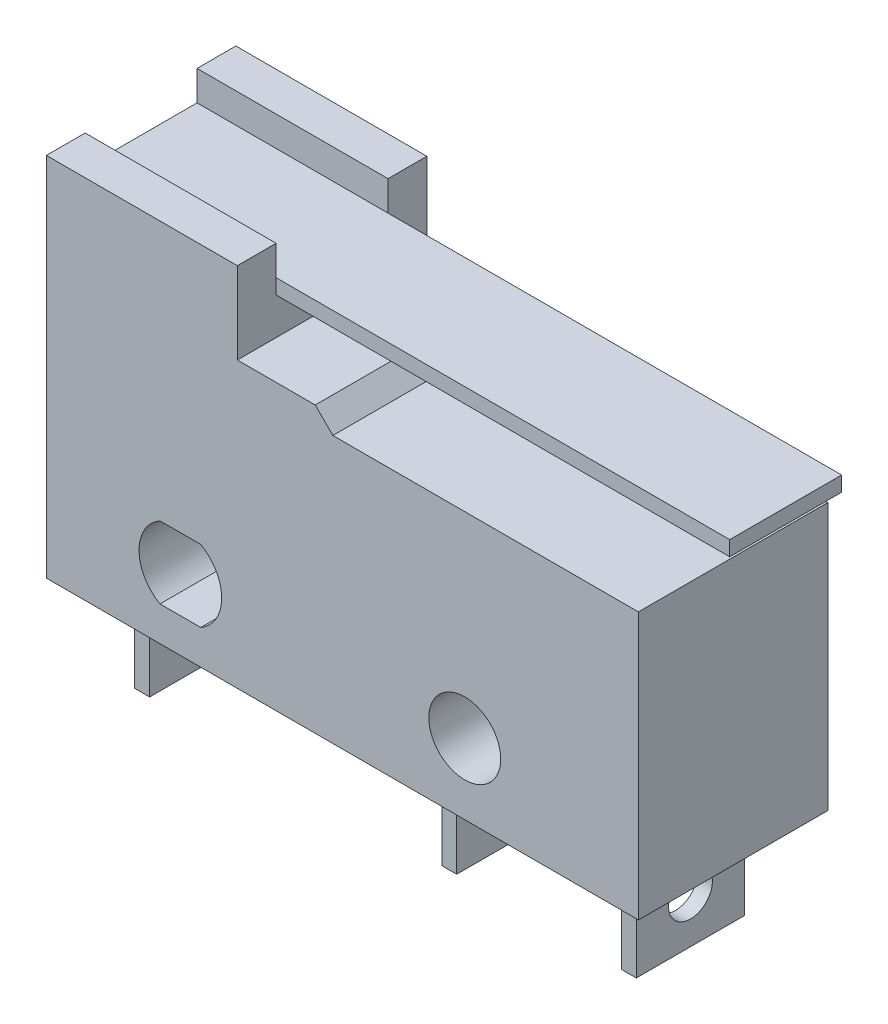
SolidWorks part; units mm, degrees
ref_plane "정면" through (0, 0, 0) normal (0, 0, 1) x (1, 0, 0)
ref_plane "윗면" through (0, 0, 0) normal (0, 1, 0) x (1, 0, 0)
ref_plane "우측면" through (0, 0, 0) normal (1, 0, 0) x (0, 0, -1)
sketch "스케치1" plane through (0, 0, 0) normal (0, 0, 1) x (1, 0, 0)
  line L0 (-10.2128, 1.205) -> (-8.8472, 1.205)
  line L1 (-14.02, -2.36) -> (5.82, -2.36)
  line L2 (-8.8472, -1.205) -> (-10.2128, -1.205)
  line L3 (5.82, -2.36) -> (5.82, 6.58)
  line L4 (5.82, 6.58) -> (-4.42, 6.58)
  line L5 (-14.02, 6.58) -> (-14.02, -2.36)
  line L6 (-4.42, 6.58) -> (-5.01, 7.17)
  line L7 (-5.01, 7.17) -> (-7.62, 7.17)
  line L8 (-7.62, 7.17) -> (-7.62, 9.908)
  line L9 (-7.62, 9.908) -> (-14.02, 9.908)
  line L10 (-14.02, 9.908) -> (-14.02, 6.58)
  circle A0 centre (0, 0) radius 1.205
  arc A1 (-10.2128, 1.205) -> (-10.2128, -1.205) centre (-9.53, 0) ccw
  arc A2 (-8.8472, -1.205) -> (-8.8472, 1.205) centre (-9.53, 0) ccw
  dimension "D1" = 2.41
  dimension "D2" = 2.77
  dimension "D3" = 2.41
  dimension "D4" = 1.205
  dimension "D5" = 9.53
  dimension "D6" = 2.36
  dimension "D7" = 8.94
  dimension "D8" = 9.53
  dimension "D9" = 12.268
  dimension "D10" = 19.84
  dimension "D11" = 7.62
  dimension "D12" = 6.4
  dimension "D13" = 45
  dimension "D14" = 9.6
extrude "보스-돌출1" add sketch "스케치1" along normal mid plane 6.35
sketch "스케치2" plane through (0, -2.36, 0) normal (0, -1, 0) x (1, 0, 0)
  line L0 (-14.02, 3.175) -> (-14.02, -3.175) construction
  line L1 (-12.42, 1.815) -> (-11.92, 1.815)
  line L2 (-12.42, 1.815) -> (-12.42, -1.815)
  line L3 (-12.42, -1.815) -> (-11.92, -1.815)
  line L4 (-11.92, 1.815) -> (-11.92, -1.815)
  line L5 (-2.13, 1.815) -> (-1.63, 1.815)
  line L6 (-2.13, 1.815) -> (-2.13, -1.815)
  line L7 (-2.13, -1.815) -> (-1.63, -1.815)
  line L8 (-1.63, 1.815) -> (-1.63, -1.815)
  line L9 (3.89, 1.815) -> (4.39, 1.815)
  line L10 (3.89, 1.815) -> (3.89, -1.815)
  line L11 (3.89, -1.815) -> (4.39, -1.815)
  line L12 (4.39, 1.815) -> (4.39, -1.815)
  point P12 (-12.17, 1.815)
  point P13 (-1.88, 1.815)
  point P14 (4.14, 1.815)
  point P17 (-12.42, 0)
  point P18 (-2.13, 0)
  point P19 (3.89, 0)
  dimension "D1" = 0.5
  dimension "D2" = 0.5
  dimension "D3" = 0.5
  dimension "D4" = 3.63
  dimension "D5" = 3.63
  dimension "D6" = 3.63
  dimension "D7" = 1.85
  dimension "D8" = 10.29
  dimension "D9" = 6.02
extrude "보스-돌출2" add sketch "스케치2" along normal blind 3.08
sketch "스케치3" plane through (-12.42, 0, 0) normal (-1, 0, 0) x (0, 0, 1)
  line L0 (-1.815, -3.9) -> (1.815, -3.9) construction
  line L1 (-1.815, -5.44) -> (-1.815, -2.36) construction
  line L2 (1.815, -5.44) -> (1.815, -2.36) construction
  circle A0 centre (0, -3.9) radius 0.735
  dimension "D1" = 1.47
extrude "컷-돌출1" cut sketch "스케치3" against normal through all
sketch "스케치4" plane through (0, 9.908, 0) normal (0, 1, 0) x (1, 0, 0)
  line L0 (-14.02, -3.175) -> (-14.02, 3.175) construction
  line L1 (-14.02, 1.875) -> (-7.62, 1.875)
  line L2 (-14.02, 1.875) -> (-14.02, -1.875)
  line L3 (-14.02, -1.875) -> (-7.62, -1.875)
  line L4 (-7.62, 1.875) -> (-7.62, -1.875)
  line L5 (-7.62, -3.175) -> (-7.62, 3.175) construction
  line L6 (-7.62, 3.175) -> (-14.02, 3.175) construction
  line L7 (-7.62, -3.175) -> (-14.02, -3.175) construction
  dimension "D1" = 1.3
  dimension "D2" = 1.3
extrude "컷-돌출2" cut sketch "스케치4" against normal blind 1
sketch "스케치6" plane through (0, 8.908, 0) normal (0, 1, 0) x (1, 0, 0)
  line L1 (-14.02, 1.875) -> (7.58, 1.875)
  line L2 (-14.02, 1.875) -> (-14.02, -1.875)
  line L3 (-14.02, -1.875) -> (7.58, -1.875)
  line L4 (7.58, 1.875) -> (7.58, -1.875)
  dimension "D1" = 21.6
extrude "보스-돌출3" add sketch "스케치6" against normal blind 0.5
sketch "Sketch4" [suppressed] plane through (0, 0, 3.175) normal (0, 0, 1) x (1, 0, 0)
  line L0 (0, 0) -> (0, 14.6071) construction
  line L2 (6.88, 14.1194) -> (6.88, 4.237) construction
  dimension "D1" = 6.88
